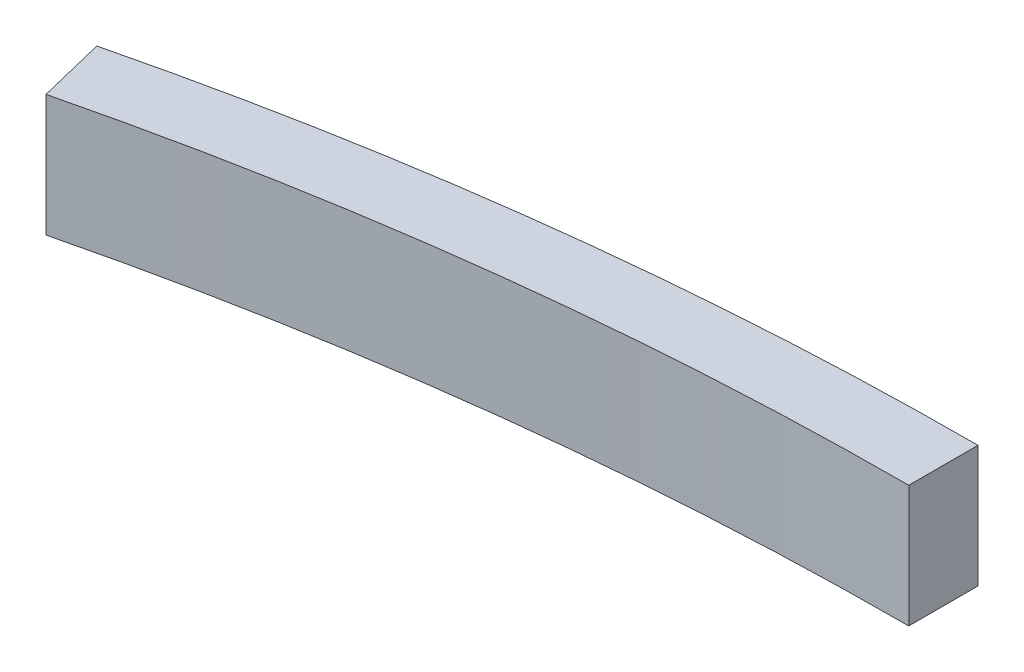
SolidWorks part; units mm, degrees
ref_plane "Front Plane" through (0, 0, 0) normal (0, 0, 1) x (1, 0, 0)
ref_plane "Top Plane" through (0, 0, 0) normal (0, 1, 0) x (1, 0, 0)
ref_plane "Right Plane" through (0, 0, 0) normal (1, 0, 0) x (0, 0, -1)
sketch "Sketch1" plane through (0, 0, 0) normal (0, 1, 0) x (1, 0, 0)
  line L0 (0, 0) -> (0, 150.2293) construction
  line L1 (0, 0) -> (-34.2537, 139.9389) construction
  line L2 (-18.0295, 73.6572) -> (-17.6521, 72.1152)
  line L3 (0, 75.8317) -> (0, 74.2442)
  arc A0 (0, 74.2442) -> (-17.6521, 72.1152) centre (0, 0) ccw
  arc A1 (0, 75.8317) -> (-18.0295, 73.6572) centre (0, 0) ccw
  dimension "D1" = 74.2442
  dimension "D2" = 1.5875
  dimension "D3" = 17.78
extrude "Boss-Extrude1" add sketch "Sketch1" along normal blind 2.794
